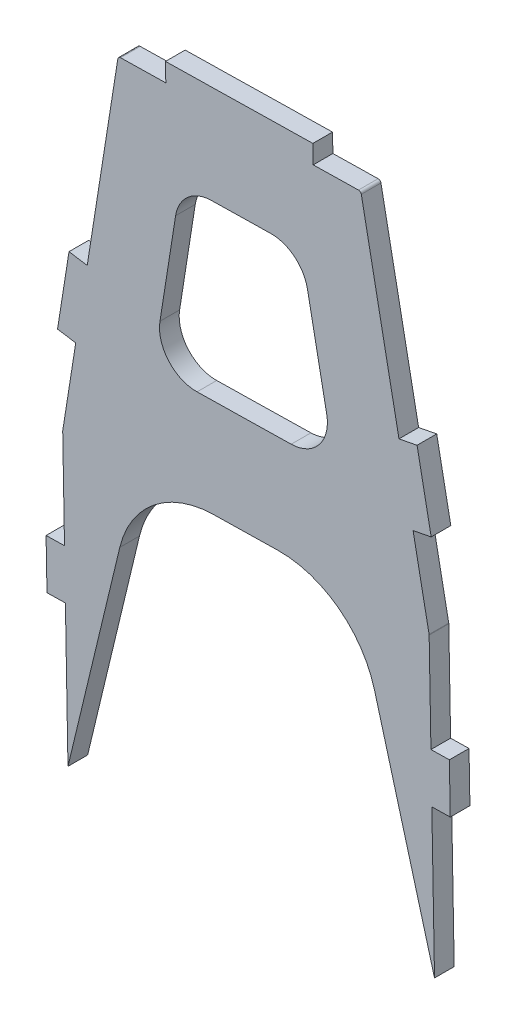
SolidWorks part; units mm, degrees
material "6061-T6 (SS)"
ref_plane "Front Plane" through (0, 0, 0) normal (0, 0, 1) x (1, 0, 0)
ref_plane "Top Plane" through (0, 0, 0) normal (0, 1, 0) x (1, 0, 0)
ref_plane "Right Plane" through (0, 0, 0) normal (1, 0, 0) x (0, 0, -1)
sketch "Sketch5" plane through (0, 0, -50.8) normal (0, 0, -1) x (-1, 0, 0)
  line L0 (-56.2179, -96.0796) -> (-52.0841, -74.9047) construction
  line L1 (38.4505, -97.8087) -> (35.0927, -76.4969) construction
  line L2 (39.7972, -75.7557) -> (35.0927, -76.4969) construction
  line L3 (39.7972, -75.7557) -> (36.8323, -56.9379) construction
  line L4 (36.8323, -56.9379) -> (32.1279, -57.6791) construction
  line L5 (-56.7584, -73.9922) -> (-52.0841, -74.9047) construction
  line L6 (-56.7584, -73.9922) -> (-53.1084, -55.2951) construction
  line L7 (-53.1084, -55.2951) -> (-48.4341, -56.2076) construction
  line L8 (-48.4341, -56.2076) -> (-38.7006, -6.3488) construction
  line L9 (-26.1883, -1.2053) -> (-26.2752, -5.967) construction
  line L10 (-37.9642, -5.7535) -> (-26.2752, -5.967) construction
  line L11 (32.1279, -57.6791) -> (24.2216, -7.4981) construction
  line L12 (23.5074, -6.8763) -> (11.8184, -6.6628) construction
  line L13 (11.9054, -1.9011) -> (11.8184, -6.6628) construction
  line L14 (-7.1414, -1.5532) -> (-26.1883, -1.2053) construction
  line L15 (-7.1414, -1.5532) -> (11.9054, -1.9011) construction
  line L16 (-56.2179, -96.0796) -> (-52.0841, -74.9047)
  line L17 (38.4505, -97.8087) -> (35.0927, -76.4969)
  line L18 (39.7972, -75.7557) -> (35.0927, -76.4969)
  line L19 (39.7972, -75.7557) -> (36.8323, -56.9379)
  line L20 (36.8323, -56.9379) -> (32.1279, -57.6791)
  line L21 (-56.7584, -73.9922) -> (-52.0841, -74.9047)
  line L22 (-56.7584, -73.9922) -> (-53.1084, -55.2951)
  line L23 (-53.1084, -55.2951) -> (-48.4341, -56.2076)
  line L24 (-48.4341, -56.2076) -> (-38.7006, -6.3488)
  line L25 (-26.1883, -1.2053) -> (-26.2752, -5.967)
  line L26 (-37.9642, -5.7535) -> (-26.2752, -5.967)
  line L27 (32.1279, -57.6791) -> (24.2216, -7.4981)
  line L28 (23.5074, -6.8763) -> (11.8184, -6.6628)
  line L29 (11.9054, -1.9011) -> (11.8184, -6.6628)
  line L30 (-7.1414, -1.5532) -> (-26.1883, -1.2053)
  line L31 (-7.1414, -1.5532) -> (11.9054, -1.9011)
  line L32 (-56.2179, -96.0796) -> (38.4505, -97.8087)
  line L33 (19.1098, -97.4554) -> (8.0462, -27.2348)
  line L34 (-23.2568, -26.6631) -> (8.0462, -27.2348)
  line L35 (-23.2568, -26.6631) -> (-36.8772, -96.4328)
  line L36 (-31.9354, -71.1188) -> (15.0957, -71.9778)
  line L37 (19.1098, -97.4554) -> (37.1017, -172.2667)
  line L38 (-36.8772, -96.4328) -> (-57.6206, -172.2667)
  line L39 (-56.6953, -121.603) -> (-56.2314, -96.2072) construction
  line L40 (37.9955, -123.3325) -> (38.4593, -97.9367) construction
  line L41 (-57.623, -172.3945) -> (-56.9272, -134.3009) construction
  line L42 (-56.9272, -134.3009) -> (-61.6889, -134.2139) construction
  line L55 (-61.457, -121.516) -> (-61.6889, -134.2139) construction
  line L56 (-56.6953, -121.603) -> (-61.457, -121.516) construction
  line L57 (-56.6953, -121.603) -> (-56.2314, -96.2072) construction
  line L58 (-57.623, -172.3945) -> (-56.9272, -134.3009)
  line L59 (-56.9272, -134.3009) -> (-61.6889, -134.2139)
  line L60 (-61.457, -121.516) -> (-61.6889, -134.2139)
  line L61 (-56.6953, -121.603) -> (-61.457, -121.516)
  line L62 (-56.6953, -121.603) -> (-56.2314, -96.2072)
  line L63 (37.0678, -174.124) -> (37.7635, -136.0304) construction
  line L64 (43.221, -98.0237) -> (42.7572, -123.4195) construction
  line L65 (37.7635, -136.0304) -> (42.5253, -136.1174) construction
  line L66 (42.7572, -123.4195) -> (42.5253, -136.1174) construction
  line L67 (37.9955, -123.3325) -> (42.7572, -123.4195) construction
  line L68 (37.9955, -123.3325) -> (38.4593, -97.9367) construction
  line L69 (37.0678, -174.124) -> (37.7635, -136.0304)
  line L70 (43.221, -98.0237) -> (42.7572, -123.4195)
  line L71 (37.7635, -136.0304) -> (42.5253, -136.1174)
  line L72 (42.7572, -123.4195) -> (42.5253, -136.1174)
  line L73 (37.9955, -123.3325) -> (42.7572, -123.4195)
  line L74 (37.9955, -123.3325) -> (38.4593, -97.9367)
  arc A0 (-37.9642, -5.7535) -> (-38.7006, -6.3488) centre (-37.9777, -6.49) ccw construction
  arc A1 (24.2216, -7.4981) -> (23.5074, -6.8763) centre (23.494, -7.6127) ccw construction
  arc A2 (-37.9642, -5.7535) -> (-38.7006, -6.3488) centre (-37.9777, -6.49) ccw
  arc A3 (24.2216, -7.4981) -> (23.5074, -6.8763) centre (23.494, -7.6127) ccw
  arc A8 (-56.2179, -96.0796) -> (-56.2314, -96.2072) centre (-55.4949, -96.2207) ccw construction
  arc A9 (-56.2179, -96.0796) -> (-56.2314, -96.2072) centre (-55.4949, -96.2207) ccw
  arc A10 (38.4593, -97.9367) -> (38.4505, -97.8087) centre (37.7228, -97.9233) ccw construction
  arc A11 (38.4593, -97.9367) -> (38.4505, -97.8087) centre (37.7228, -97.9233) ccw
  dimension "D1" = 19.05
  dimension "D2" = 19.05
  dimension "D3" = 25.4
  dimension "D4" = 25.4
  dimension "D5" = 76.2
extrude "Boss-Extrude2" add sketch "Sketch5" along normal blind 5.08
fillet "Fillet2" radius 9.525 4 edges at (23.2568, -26.6631, -53.34) (-8.0462, -27.2348, -53.34) (31.9354, -71.1188, -53.34) (-15.0957, -71.9778, -53.34)
fillet "Fillet3" radius 25.4 2 edges at (-19.1098, -97.4554, -53.34) (36.8772, -96.4328, -53.34)
